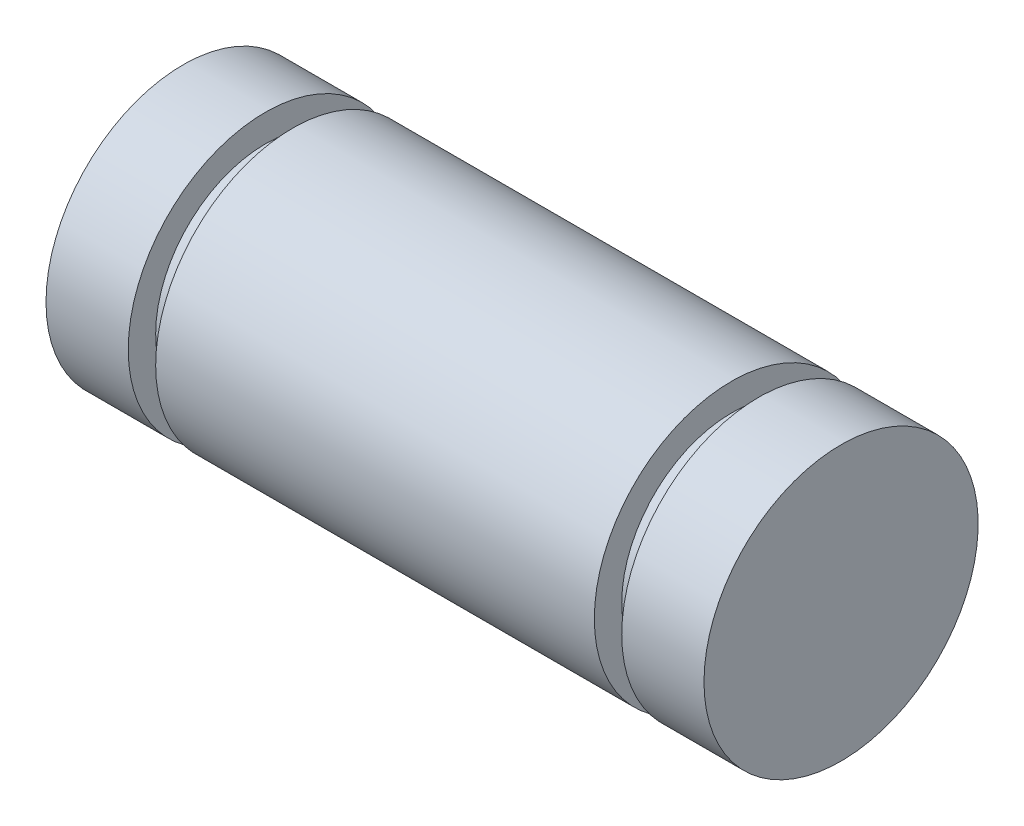
SolidWorks part; units mm, degrees
ref_plane "Front Plane" through (0, 0, 0) normal (0, 0, 1) x (1, 0, 0)
ref_plane "Top Plane" through (0, 0, 0) normal (0, 1, 0) x (1, 0, 0)
ref_plane "Right Plane" through (0, 0, 0) normal (1, 0, 0) x (0, 0, -1)
sketch "Sketch1" plane through (0, 0, 0) normal (0, 0, 1) x (1, 0, 0)
  line L0 (0, 0) -> (12, 0)
  line L1 (12, 0) -> (12, 2.5)
  line L2 (12, 2.5) -> (10.5, 2.5)
  line L3 (10.5, 2.5) -> (10.5, 2)
  line L4 (10.5, 2) -> (10, 2)
  line L5 (10, 2) -> (10, 2.5)
  line L6 (10, 2.5) -> (2, 2.5)
  line L7 (2, 2.5) -> (2, 2)
  line L8 (2, 2) -> (1.5, 2)
  line L9 (1.5, 2) -> (1.5, 2.5)
  line L10 (1.5, 2.5) -> (0, 2.5)
  line L11 (0, 2.5) -> (0, 0)
  dimension "D1" = 12
revolve "Revolve1" add sketch "Sketch1" angle 360 about L0
